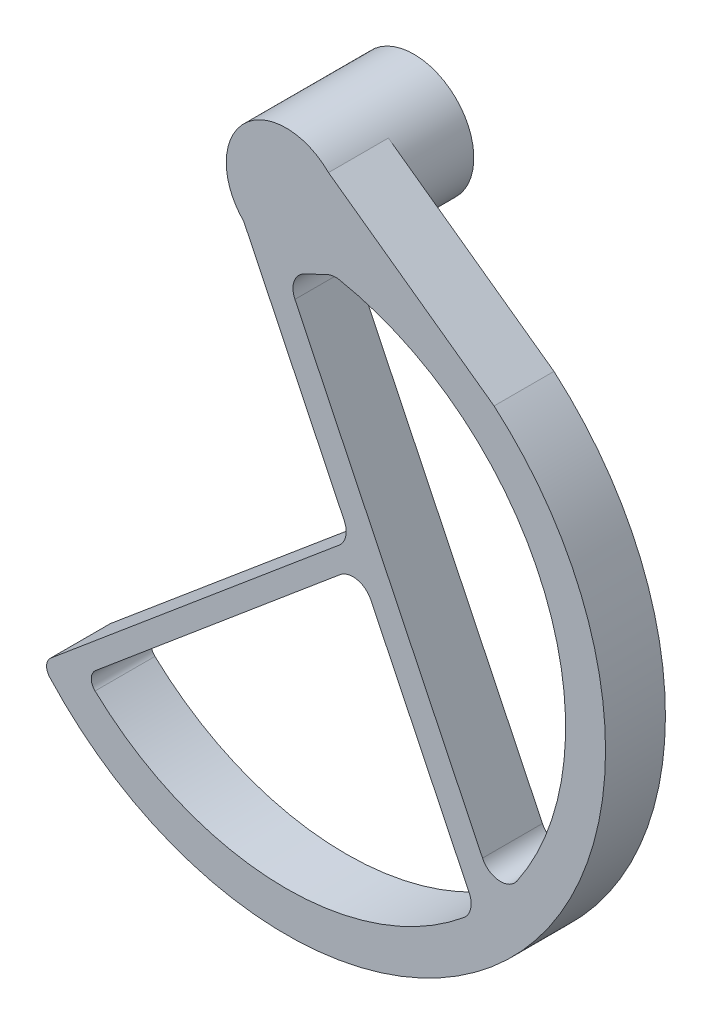
SolidWorks part; units mm, degrees
ref_plane "正面" through (0, 0, 0) normal (0, 0, 1) x (1, 0, 0)
ref_plane "平面" through (0, 0, 0) normal (0, 1, 0) x (1, 0, 0)
ref_plane "右側面" through (0, 0, 0) normal (1, 0, 0) x (0, 0, -1)
sketch "ｽｹｯﾁ4" plane through (0, 0, 0) normal (0, 0, 1) x (1, 0, 0)
  line L0 (0, 0.7897) -> (0, 0)
  line L1 (-53.6231, -124.9951) -> (-58.9406, -129.4571)
  line L3 (-10.6066, -10.6066) -> (14.5363, -62.8896)
  line L4 (-53.6231, -124.9951) -> (13.2442, -68.8868)
  line L5 (21.2324, -76.8138) -> (45.8448, -127.9938)
  line L6 (10.6066, 10.6066) -> (52.0762, -19.2705)
  line L7 (-58.0696, -135.2532) -> (-57.9498, -135.1527)
  line L8 (-47.7477, -126.5866) -> (13.5112, -75.1515)
  arc A1 (-59.2335, -133.7716) -> (52.0762, -19.2705) centre (0, -80) ccw
  arc A2 (-47.8702, -131.073) -> (44.5187, -134.0193) centre (0, -80) ccw
  arc A3 (10.6066, 10.6066) -> (-10.6066, -10.6066) centre (0, 0) ccw
  arc A4 (-59.2335, -133.7716) -> (-58.9406, -129.4571) centre (-57.0123, -131.7552) cw
  arc A5 (-47.8702, -131.073) -> (-47.7477, -126.5866) centre (-45.8186, -128.8841) cw
  arc A6 (13.5112, -75.1515) -> (21.2324, -76.8138) centre (16.7264, -78.9807) cw
  arc A7 (13.2442, -68.8868) -> (14.5363, -62.8896) centre (10.0302, -65.0566) ccw
  arc A8 (45.8448, -127.9938) -> (44.5187, -134.0193) centre (41.3388, -130.1608) cw
  point P18 (-61.2836, -131.423)
  point P21 (-50.2744, -128.7081)
  point P24 (18.4421, -71.0114)
  dimension "D3" = 140
  dimension "D4" = 30
  dimension "D5" = 5
  dimension "D6" = 3
  dimension "D7" = 3
  dimension "D8" = 5
  dimension "D9" = 5
  dimension "D10" = 5
  dimension "D2" = 5
extrude "ﾎﾞｽ - 押し出し1" add sketch "ｽｹｯﾁ4" along normal blind 15
sketch "ｽｹｯﾁ6" plane through (0, 0, 15) normal (0, 0, 1) x (1, 0, 0)
  line L6 (49.1896, -118.7973) -> (2.2018, -21.089)
  line L7 (6.4834, -13.4819) -> (4.5408, -14.416)
  line L8 (6.4834, -13.4819) -> (10.2197, -11.6851)
  arc A0 (57.8261, -119.448) -> (13.3394, -11.2828) centre (0, -80) ccw
  arc A1 (2.2018, -21.089) -> (4.5408, -14.416) centre (6.7078, -18.9221) cw
  arc A2 (13.3394, -11.2828) -> (10.2197, -11.6851) centre (12.3866, -16.1911) ccw
  arc A3 (57.8261, -119.448) -> (49.1896, -118.7973) centre (53.6956, -116.6303) cw
  point P7 (0.0348, -16.583)
  point P14 (52.6925, -126.0814)
  dimension "D3" = 121.502
  dimension "D4" = 70
  dimension "D1" = 5
  dimension "D2" = 5
  dimension "D5" = 5
  dimension "D6" = 90
extrude "ｶｯﾄ - 押し出し1" cut sketch "ｽｹｯﾁ6" against normal blind 15
sketch "ｽｹｯﾁ11" plane through (0, 0, 0) normal (0, 0, -1) x (-1, 0, 0)
  circle A0 centre (0, 0) radius 15
extrude "ﾎﾞｽ - 押し出し3" add sketch "ｽｹｯﾁ11" along normal blind 17
sketch "ｽｹｯﾁ12" plane through (0, 0, -17) normal (0, 0, -1) x (-1, 0, 0)
  circle A0 centre (0, 0) radius 10.1
extrude "ｶｯﾄ - 押し出し5" cut sketch "ｽｹｯﾁ12" against normal blind 2
